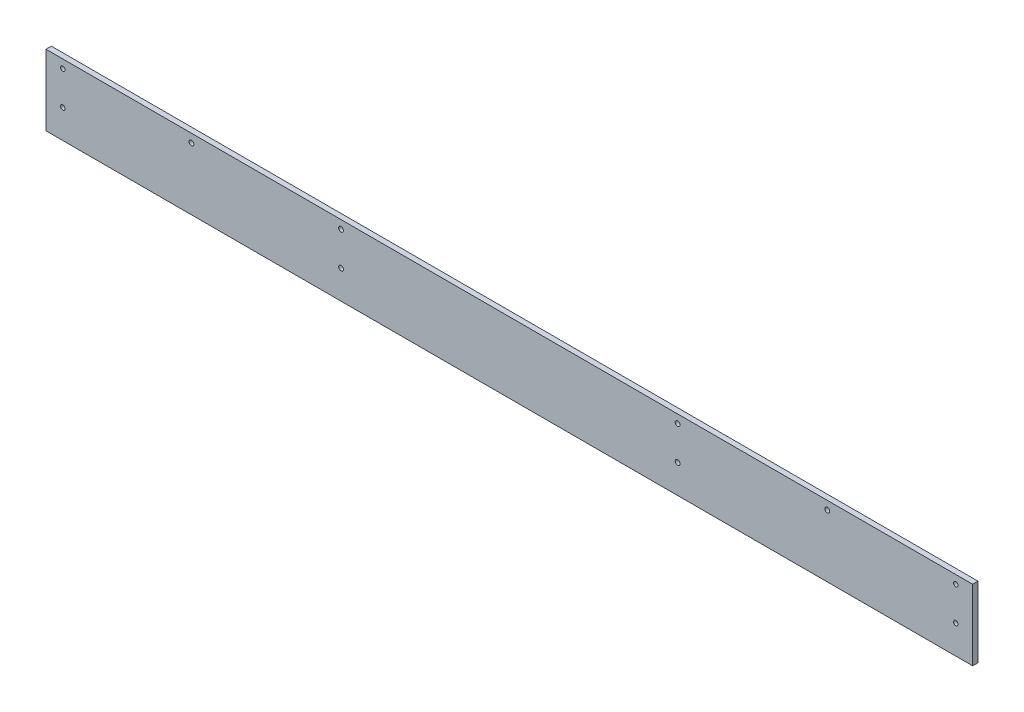
SolidWorks part; units mm, degrees
material "ABS PC"
ref_plane "Front Plane" through (0, 0, 0) normal (0, 0, 1) x (1, 0, 0)
ref_plane "Top Plane" through (0, 0, 0) normal (0, 1, 0) x (1, 0, 0)
ref_plane "Right Plane" through (0, 0, 0) normal (1, 0, 0) x (0, 0, -1)
sketch "Sketch3" plane through (0, 0, 0) normal (0, 0, 1) x (1, 0, 0)
  line L1 (-275.35, 15) -> (275.35, 15)
  line L2 (-275.35, 15) -> (-275.35, -15)
  line L3 (-275.35, -15) -> (275.35, -15)
  line L4 (275.35, 15) -> (275.35, -15)
  line L5 (-275.35, 15) -> (275.35, -15) construction
  line L6 (-275.35, -15) -> (275.35, 15) construction
  point P0 (0, 0)
  dimension "D1" = 550.7
  dimension "D2" = 30
extrude "Boss-Extrude3" add sketch "Sketch3" along normal blind 3.18
sketch "Sketch4" plane through (0, 0, 3.18) normal (0, 0, 1) x (1, 0, 0)
  line L0 (275.35, 0) -> (-275.35, 0) construction
  line L1 (275.35, -15) -> (275.35, 15) construction
  line L2 (-275.35, 15) -> (-275.35, -15) construction
  line L3 (0, 15) -> (0, 0) construction
  line L4 (275.35, 15) -> (-275.35, 15) construction
  line L5 (0, 0) -> (0, -15) construction
  line L6 (-275.35, -15) -> (275.35, -15) construction
  line L7 (275.35, 15) -> (275.35, 0) construction
  line L8 (275.35, 0) -> (275.35, -15) construction
  line L9 (265.35, 15) -> (265.35, 0) construction
  circle A0 centre (265.35, 10) radius 1.35
  point P19 (0, 0)
  dimension "D2" = 2.7
  dimension "D3" = 10
  dimension "D1" = 5
extrude "Cut-Extrude1" cut sketch "Sketch4" against normal up to next
mirror "Mirror1" about plane through (0, 0, 0) normal (0, 1, 0) of "Cut-Extrude1"
mirror "Mirror2" about plane through (0, 0, 0) normal (1, 0, 0) of "Mirror1", "Cut-Extrude1"
sketch "Sketch5" plane through (0, 0, 3.18) normal (0, 0, 1) x (1, 0, 0)
  line L0 (0, -10) -> (100, -10) construction
  line L1 (-275.35, -15) -> (275.35, -15) construction
  circle A0 centre (100, -10) radius 1.425
  dimension "D2" = 2.85
  dimension "D1" = 100
  dimension "D3" = 5
extrude "Cut-Extrude2" cut sketch "Sketch5" against normal up to next
mirror "Mirror3" about plane through (0, 0, 0) normal (1, 0, 0) of "Cut-Extrude2"
mirror "Mirror4" about plane through (0, 0, 0) normal (0, 1, 0) of "Mirror3", "Cut-Extrude2"
sketch "Sketch6" plane through (0, -15, 0) normal (0, -1, 0) x (1, 0, 0)
  line L1 (-275.35, 3.18) -> (275.35, 3.18)
  line L2 (-275.35, 3.18) -> (-275.35, 0)
  line L3 (-275.35, 0) -> (275.35, 0)
  line L4 (275.35, 3.18) -> (275.35, 0)
extrude "Boss-Extrude4" add sketch "Sketch6" along normal blind 12
sketch "Sketch7" plane through (0, 0, 3.18) normal (0, 0, 1) x (1, 0, 0)
  line L0 (275.35, 15) -> (-275.35, 15) construction
  circle A0 centre (-188.94, 10) radius 1.45
  dimension "D2" = 2.9
  dimension "D1" = 5
extrude "Cut-Extrude3" cut sketch "Sketch7" against normal up to next
mirror "Mirror5" about plane through (0, 0, 0) normal (1, 0, 0) of "Cut-Extrude3"
